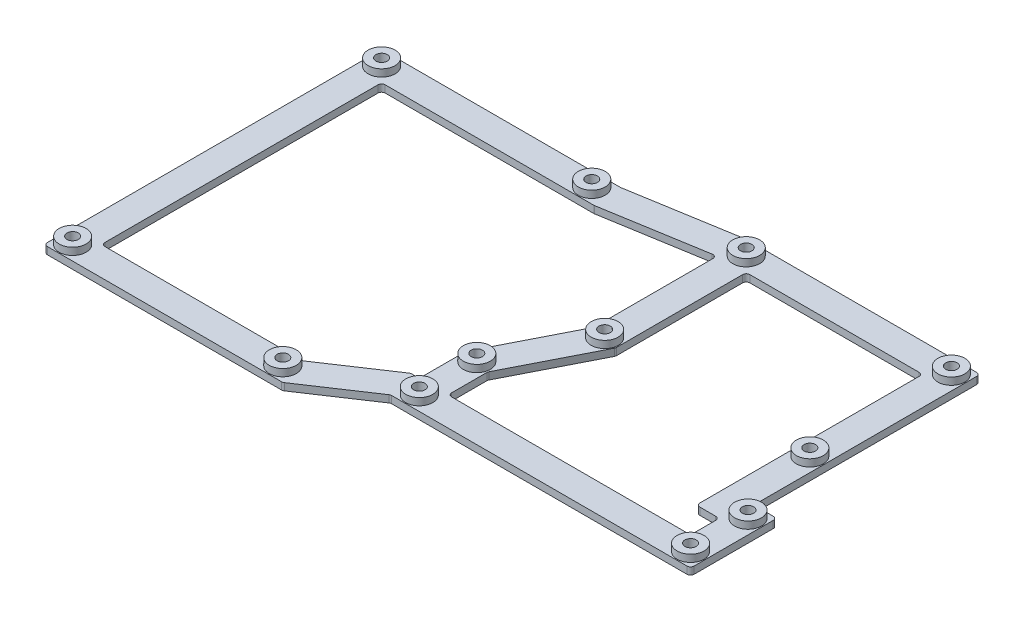
SolidWorks part; units mm, degrees
ref_plane "Front Plane" through (0, 0, 0) normal (0, 0, 1) x (1, 0, 0)
ref_plane "Top Plane" through (0, 0, 0) normal (0, 1, 0) x (1, 0, 0)
ref_plane "Right Plane" through (0, 0, 0) normal (1, 0, 0) x (0, 0, -1)
sketch "Sketch1" plane through (0, 0, 0) normal (0, 1, 0) x (1, 0, 0)
  line L0 (0, 0) -> (85, 0) construction
  line L5 (-85, -50) -> (85, -50) construction
  line L6 (-85, -50) -> (-85, 50) construction
  line L7 (-85, 50) -> (85, 50) construction
  line L8 (85, -50) -> (85, 50) construction
  line L9 (-85, -50) -> (85, 50) construction
  line L10 (-85, 50) -> (85, -50) construction
  line L11 (15.5, 45) -> (72.6, 45) construction
  line L12 (15.5, 45) -> (15.5, 5.6) construction
  line L13 (15.5, 5.6) -> (72.6, 5.6) construction
  line L14 (72.6, 45) -> (72.6, 5.6) construction
  line L15 (-81, 40) -> (-22.5, 40) construction
  line L16 (-81, 40) -> (-81, -46) construction
  line L17 (-81, -46) -> (-22.5, -46) construction
  line L18 (-22.5, 40) -> (-22.5, -46) construction
  line L19 (76.6, -14) -> (83, -14)
  line L20 (79, -34) -> (3.5, -34) construction
  line L21 (79, -34) -> (79, -18) construction
  line L22 (79, -18) -> (3.5, -18) construction
  line L23 (3.5, -34) -> (3.5, -18) construction
  line L25 (-85, 44) -> (-85, -50)
  line L26 (-85, -50) -> (-18.5, -50)
  line L31 (76.6, 49) -> (76.6, -14)
  line L34 (-0.5, -38) -> (83, -38)
  line L35 (83, -14) -> (83, -38)
  line L36 (-0.5, -38) -> (-18.5, -50)
  line L37 (76.6, 49) -> (11.5, 49)
  line L38 (-85, 44) -> (-18.5, 44)
  line L39 (11.5, 49) -> (-18.5, 44)
  circle A0 centre (15.5, 45) radius 1.58
  circle A1 centre (72.6, 45) radius 1.58
  circle A2 centre (72.6, 5.6) radius 1.58
  circle A3 centre (15.5, 5.6) radius 1.58
  circle A4 centre (-81, 40) radius 1.58
  circle A5 centre (-22.5, 40) radius 1.58
  circle A6 centre (-22.5, -46) radius 1.58
  circle A7 centre (-81, -46) radius 1.58
  circle A8 centre (79, -34) radius 1.58
  circle A9 centre (79, -18) radius 1.58
  circle A10 centre (3.5, -34) radius 1.58
  circle A11 centre (3.5, -18) radius 1.58
  point P0 (0, 0)
  dimension "D4" = 3.16
  dimension "D8" = 3.16
  dimension "D17" = 3.16
  dimension "D1" = 100
  dimension "D2" = 170
  dimension "D3" = 39.4
  dimension "D5" = 57.1
  dimension "D6" = 86
  dimension "D7" = 58.5
  dimension "D9" = 4
  dimension "D10" = 4
  dimension "D11" = 38
  dimension "D12" = 5
  dimension "D13" = 16
  dimension "D14" = 75.5
  dimension "D15" = 16
  dimension "D16" = 6
  dimension "D18" = 4
  dimension "D19" = 4
  dimension "D20" = 4
  dimension "D21" = 4
  dimension "D22" = 4
  dimension "D23" = 4
  dimension "D24" = 4
  dimension "D25" = 4
  dimension "D26" = 4
  dimension "D27" = 4
  dimension "D28" = 4
  dimension "D29" = 4
extrude "Boss-Extrude1" add sketch "Sketch1" along normal blind 2
fillet "Fillet1" [suppressed] radius 2
sketch "Sketch2" plane through (0, 2, 0) normal (0, 1, 0) x (1, 0, 0)
  circle A36 centre (-81, 40) radius 3.75
  circle A37 centre (-22.5, 40) radius 3.75
  circle A38 centre (-81, -46) radius 3.75
  circle A39 centre (-22.5, -46) radius 3.75
  circle A40 centre (3.5, -34) radius 3.75
  circle A41 centre (3.5, -18) radius 3.75
  circle A42 centre (15.5, 5.6) radius 3.75
  circle A43 centre (72.6, 5.6) radius 3.75
  circle A44 centre (79, -18) radius 3.75
  circle A45 centre (79, -34) radius 3.75
  circle A46 centre (72.6, 45) radius 3.75
  circle A47 centre (15.5, 45) radius 3.75
  circle A48 centre (72.6, 45) radius 1.58 construction
  circle A49 centre (72.6, 5.6) radius 1.58 construction
  circle A50 centre (79, -34) radius 1.58 construction
  circle A51 centre (79, -18) radius 1.58 construction
  circle A52 centre (3.5, -34) radius 1.58 construction
  circle A53 centre (3.5, -18) radius 1.58 construction
  circle A54 centre (15.5, 5.6) radius 1.58 construction
  circle A55 centre (-22.5, 40) radius 1.58 construction
  circle A56 centre (-22.5, -46) radius 1.58 construction
  circle A57 centre (-81, -46) radius 1.58 construction
  circle A58 centre (-81, 40) radius 1.58 construction
  circle A59 centre (72.6, 45) radius 1.58
  circle A60 centre (72.6, 5.6) radius 1.58
  circle A61 centre (79, -34) radius 1.58
  circle A62 centre (79, -18) radius 1.58
  circle A63 centre (3.5, -34) radius 1.58
  circle A64 centre (3.5, -18) radius 1.58
  circle A65 centre (15.5, 5.6) radius 1.58
  circle A66 centre (-22.5, 40) radius 1.58
  circle A67 centre (-22.5, -46) radius 1.58
  circle A68 centre (-81, -46) radius 1.58
  circle A69 centre (-81, 40) radius 1.58
  circle A70 centre (15.5, 45) radius 1.58 construction
  circle A71 centre (15.5, 45) radius 1.58
  dimension "D1" = 7.5
extrude "Boss-Extrude2" add sketch "Sketch2" along normal blind 2
sketch "Sketch7" plane through (0, 2, 0) normal (0, 1, 0) x (1, 0, 0)
  line L0 (11.5, 6.5585) -> (19.5, 4.6415) construction
  line L13 (-0.5, -17.0415) -> (7.5, -18.9585) construction
  line L23 (-0.5, -17.0415) -> (11.5, 6.5585)
  line L24 (19.5, 4.6415) -> (19.5, 41)
  line L25 (19.5, 4.6415) -> (7.5, -18.9585)
  line L26 (7.5, -18.9585) -> (7.5, -30)
  line L27 (7.5, -30) -> (75, -30)
  line L28 (19.5, 41) -> (68.6, 41)
  line L29 (11.5, 6.5585) -> (11.5, 40.8896)
  line L30 (11.5, 40.8896) -> (-17.8379, 36)
  line L31 (15.5, 45) -> (15.5, 5.6) construction
  line L32 (-17.8379, 36) -> (-77, 36)
  line L33 (-77, 36) -> (-77, -42)
  line L34 (-77, -42) -> (-20.9222, -42)
  line L35 (-20.9222, -42) -> (-2.9222, -30)
  line L36 (-2.9222, -30) -> (75, -30)
  line L37 (75, -30) -> (75, -22)
  line L38 (75, -22) -> (68.6, -22)
  line L39 (68.6, -22) -> (68.6, 41)
  line L40 (68.6, 41) -> (12.1621, 41)
  line L41 (12.1621, 41) -> (-17.8379, 36)
  line L42 (-17.8379, 36) -> (-77, 36)
  line L43 (-77, 36) -> (-77, -42)
  line L44 (-77, -42) -> (-20.9222, -42)
  line L45 (-20.9222, -42) -> (-2.9222, -30)
  line L46 (-2.9222, -30) -> (75, -30) construction
  line L47 (75, -30) -> (75, -22)
  line L48 (75, -22) -> (68.6, -22)
  line L49 (68.6, -22) -> (68.6, 41)
  line L50 (68.6, 41) -> (12.1621, 41) construction
  line L51 (12.1621, 41) -> (-17.8379, 36) construction
  line L52 (-0.5, -17.0415) -> (-0.5, -30)
  line L53 (-2.9222, -30) -> (-0.5, -30)
  line L54 (3.5, -18) -> (3.5, -34) construction
  dimension "D1" = 8
  dimension "D2" = 8
  dimension "D3" = 8
  dimension "D4" = 8
extrude "Cut-Extrude5" cut sketch "Sketch7" against normal through all
fillet "Fillet4" radius 1 27 edges at (11.5, 1, -49) (-18.5, 1, -44) (-85, 1, -44) (-85, 1, 50) (-18.5, 1, 50) (-0.5, 1, 38) (83, 1, 38) (83, 1, 14) (76.6, 1, 14) (76.6, 1, -49) (68.6, 1, -41) (68.6, 1, 22) (75, 1, 22) (75, 1, 30) (7.5, 1, 30) (7.5, 1, 18.9585) (19.5, 1, -4.6415) (19.5, 1, -41) (11.5, 1, -40.8896) (11.5, 1, -6.5585) (-17.8379, 1, -36) (-77, 1, -36) (-77, 1, 42) (-20.9222, 1, 42) (-0.5, 1, 17.0415) (-2.9222, 1, 30) (-0.5, 1, 30)
equation "\"D19@Sketch1\"=\"D18@Sketch1\""
equation "\"D20@Sketch1\"=\"D18@Sketch1\""
equation "\"D21@Sketch1\"=\"D18@Sketch1\""
equation "\"D22@Sketch1\"=\"D18@Sketch1\""
equation "\"D23@Sketch1\"=\"D18@Sketch1\""
equation "\"D24@Sketch1\"=\"D18@Sketch1\""
equation "\"D25@Sketch1\"=\"D18@Sketch1\""
equation "\"D26@Sketch1\"=\"D18@Sketch1\""
equation "\"D27@Sketch1\"=\"D18@Sketch1\""
equation "\"D28@Sketch1\"=\"D18@Sketch1\""
equation "\"D29@Sketch1\"=\"D18@Sketch1\""
